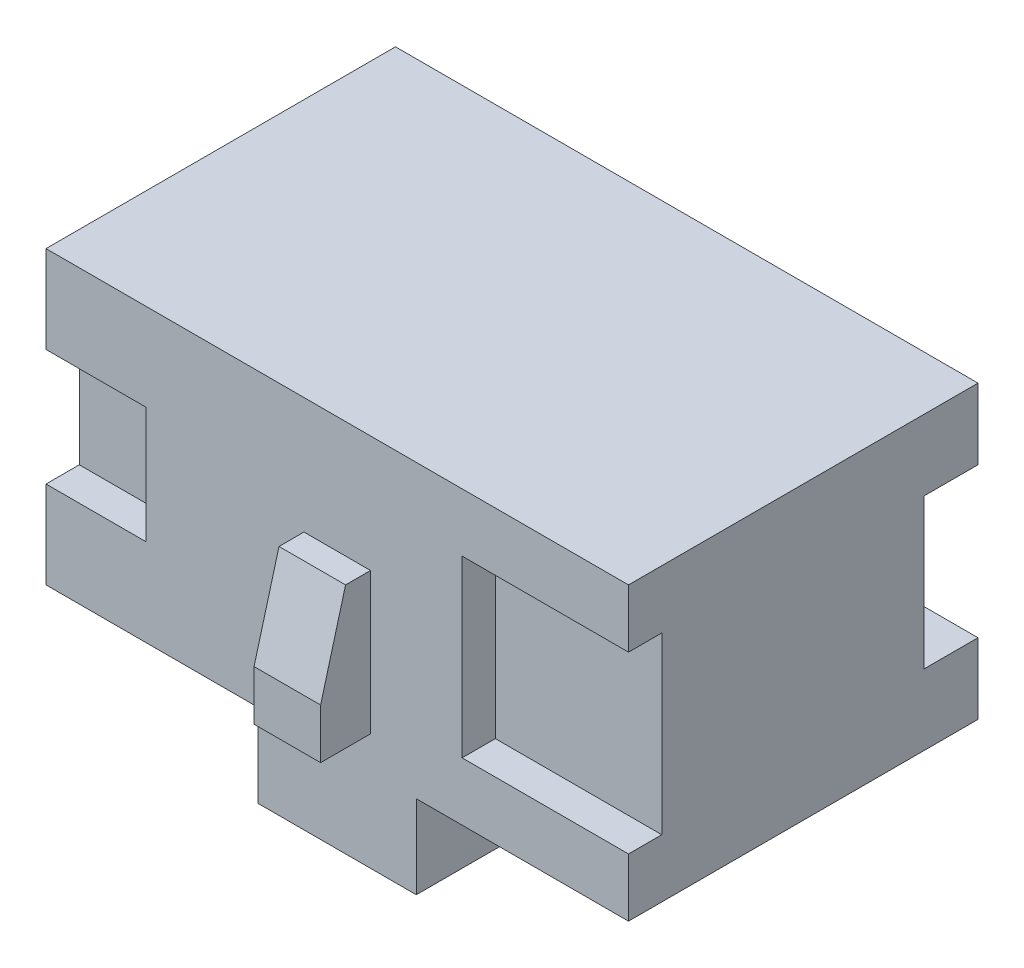
SolidWorks part; units mm, degrees
ref_plane "Спереди" through (0, 0, 0) normal (0, 0, 1) x (1, 0, 0)
ref_plane "Сверху" through (0, 0, 0) normal (0, 1, 0) x (1, 0, 0)
ref_plane "Справа" through (0, 0, 0) normal (1, 0, 0) x (0, 0, -1)
sketch "Эскиз1" plane through (0, 0, 0) normal (0, 0, 1) x (1, 0, 0)
  line L1 (-35, -17.5) -> (35, -17.5)
  line L2 (-35, -17.5) -> (-35, 17.5)
  line L3 (-35, 17.5) -> (35, 17.5)
  line L4 (35, -17.5) -> (35, 17.5)
  line L5 (-35, -17.5) -> (35, 17.5) construction
  line L6 (-35, 17.5) -> (35, -17.5) construction
  line L7 (-9.5, -27.5) -> (9.5, -27.5)
  line L8 (-9.5, -27.5) -> (-9.5, -17.5)
  line L9 (-9.5, -17.5) -> (9.5, -17.5)
  line L10 (9.5, -27.5) -> (9.5, -17.5)
  line L11 (-9.5, -27.5) -> (9.5, -17.5) construction
  line L12 (-9.5, -17.5) -> (9.5, -27.5) construction
  point P0 (0, 0)
  point P6 (0, -22.5)
  dimension "D1" = 70
  dimension "D2" = 35
  dimension "D3" = 10
  dimension "D4" = 19
extrude "Бобышка-Вытянуть1" add sketch "Эскиз1" along normal blind 42 contours L7 L10 L1 L8 | L1 L4 L3 L2
sketch "Эскиз2" plane through (35, 0, 0) normal (1, 0, 0) x (0, 0, -1)
  line L0 (0, 0) -> (-42, 0) construction
  line L1 (0, -17.5) -> (0, 17.5) construction
  line L2 (-42, -17.5) -> (-42, 17.5) construction
  line L3 (-6.5, 9) -> (0, 9)
  line L4 (-6.5, 9) -> (-6.5, -9)
  line L5 (0, 9) -> (0, -9)
  line L6 (-6.5, -9) -> (0, -9)
  point P12 (-6.5, 0)
  dimension "D1" = 9
  dimension "D2" = 6.5
extrude "Вырез-Вытянуть1" cut sketch "Эскиз2" against normal through all
sketch "Эскиз3" plane through (0, 0, 42) normal (0, 0, 1) x (1, 0, 0)
  line L0 (-35, 0) -> (35, 0) construction
  line L1 (-35, -17.5) -> (-35, 17.5) construction
  line L2 (35, -17.5) -> (35, 17.5) construction
  line L4 (35, -10.5) -> (15, -10.5)
  line L5 (35, -10.5) -> (35, 10.5)
  line L6 (35, 10.5) -> (15, 10.5)
  line L7 (15, -10.5) -> (15, 10.5)
  line L8 (35, -10.5) -> (15, 10.5) construction
  line L9 (35, 10.5) -> (15, -10.5) construction
  line L10 (-23, -7) -> (-35, -7)
  line L11 (-23, -7) -> (-23, 7)
  line L12 (-23, 7) -> (-35, 7)
  line L13 (-35, -7) -> (-35, 7)
  line L14 (-23, -7) -> (-35, 7) construction
  line L15 (-23, 7) -> (-35, -7) construction
  point P6 (25, 0)
  point P11 (-29, 0)
  dimension "D1" = 21
  dimension "D2" = 20
  dimension "D3" = 14
  dimension "D4" = 12
extrude "Вырез-Вытянуть2" cut sketch "Эскиз3" against normal blind 4
sketch "Эскиз4" plane through (0, 0, 0) normal (1, 0, 0) x (0, 0, -1)
  line L0 (-42, 10.5) -> (-42, -10.5) construction
  line L1 (-42, -13.5) -> (-48, -13.5)
  line L2 (-42, -13.5) -> (-42, 3.5)
  line L3 (-42, 3.5) -> (-48, 3.5)
  line L4 (-48, -13.5) -> (-48, 3.5)
  line L6 (-42, -17.5) -> (0, -17.5) construction
  line L7 (-45, 3.5) -> (-48, -7.5)
  dimension "D1" = 6
  dimension "D2" = 4
  dimension "D3" = 17
  dimension "D4" = 11
extrude "Бобышка-Вытянуть2" add sketch "Эскиз4" along normal blind 4 and the other way blind 4 contours L3 L7 L4 L1 L2
